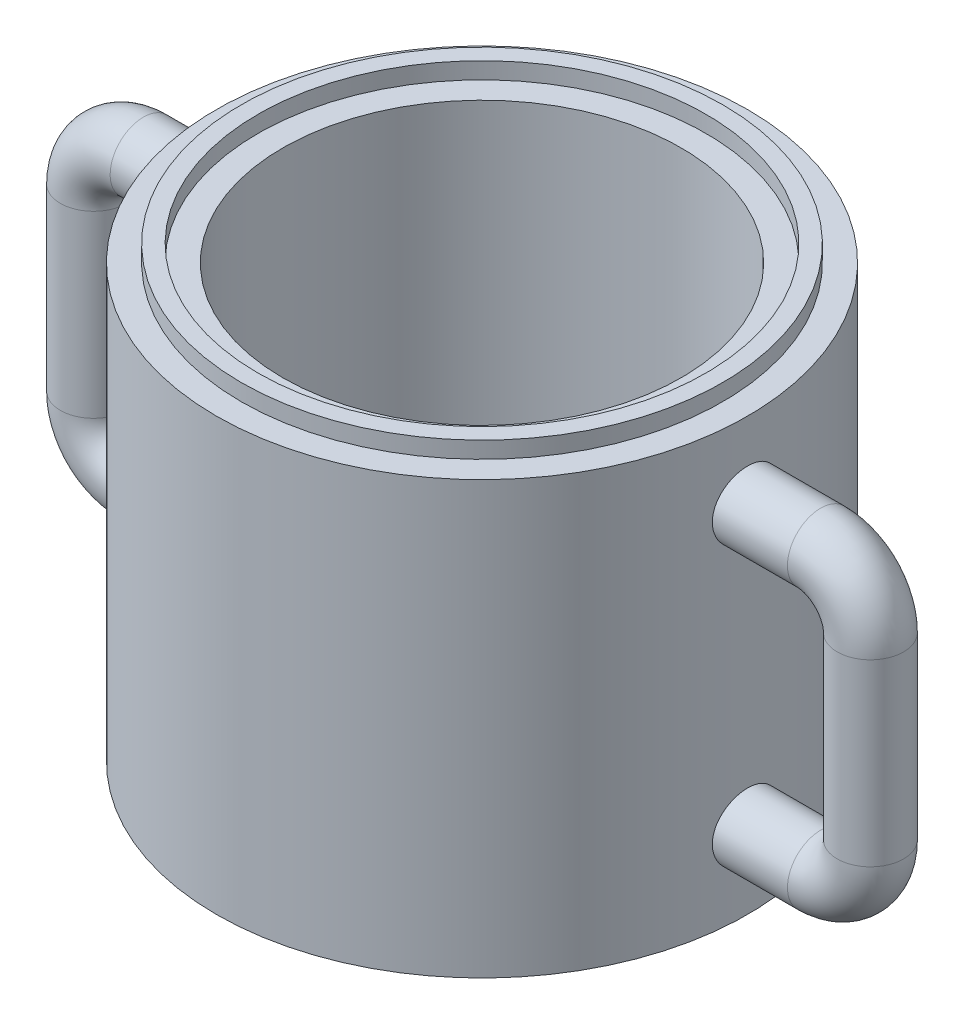
SolidWorks part; units mm, degrees
ref_plane "Plano frontal" through (0, 0, 0) normal (0, 0, 1) x (1, 0, 0)
ref_plane "Plano superior" through (0, 0, 0) normal (0, 1, 0) x (1, 0, 0)
ref_plane "Plano direito" through (0, 0, 0) normal (1, 0, 0) x (0, 0, -1)
sketch "Esboço1" plane through (0, 0, 0) normal (0, 1, 0) x (1, 0, 0)
  circle A0 centre (0, 0) radius 80
  dimension "D1" = 160
extrude "Ressalto-extrusão1" add sketch "Esboço1" along normal blind 130
sketch "Esboço2" plane through (0, 130, 0) normal (0, 1, 0) x (1, 0, 0)
  circle A0 centre (0, 0) radius 60
  dimension "D1" = 120
extrude "Corte-extrusão1" cut sketch "Esboço2" against normal blind 100
sketch "Esboço4" plane through (0, 0, 0) normal (1, 0, 0) x (0, 0, -1)
  line L0 (-80, 130) -> (-72.5, 130) construction
  line L2 (80, 130) -> (-80, 130) construction
  line L3 (-72.5, 130) -> (-67.5, 130) construction
  line L4 (-67.5, 130) -> (-60, 130) construction
  line L5 (-72.5, 130) -> (-72.5, 135)
  line L6 (-72.5, 135) -> (-67.5, 135)
  line L7 (-67.5, 135) -> (-67.5, 130)
  line L8 (-67.5, 130) -> (-72.5, 130)
  line L9 (0, 130) -> (0, 0) construction
  line L10 (60, 130) -> (-60, 130) construction
  dimension "D1" = 7.5
  dimension "D2" = 5
  dimension "D3" = 5
revolve "Revolução1" add sketch "Esboço4" angle 360 about L9
ref_plane "Plano1" through (70, 0, 0) normal (1, 0, 0) x (0, 0, -1)
sketch "Esboço5" plane through (70, 0, 0) normal (1, 0, 0) x (0, 0, -1)
  line L0 (-80, 130) -> (80, 130) construction
  line L1 (0, 130) -> (0, 0) construction
  line L2 (0, 65) -> (80, 65) construction
  line L3 (80, 0) -> (80, 130) construction
  circle A0 centre (0, 107) radius 12.5
  circle A1 centre (0, 23) radius 12.5
  dimension "D1" = 25
  dimension "D2" = 23
sketch "Esboço6" plane through (0, 0, 0) normal (0, 0, 1) x (1, 0, 0)
  line L0 (70, 107) -> (102, 107)
  line L1 (70, 23) -> (102, 23)
  line L2 (117, 92) -> (117, 38)
  arc A0 (102, 23) -> (117, 38) centre (102, 38) ccw
  arc A1 (102, 107) -> (117, 92) centre (102, 92) cw
  point P8 (117, 23)
  point P11 (117, 107)
  dimension "D3" = 15
  dimension "D1" = 47
  dimension "D2" = 47
sweep "Varredura2" add path "Esboço6" circular profile diameter 20 parameters "D3"=20
ref_plane "Plano2" through (-70, 0, 0) normal (1, 0, 0) x (0, 0, -1)
sketch "Esboço35" plane through (-70, 0, 0) normal (1, 0, 0) x (0, 0, -1)
  line L0 (-80, 130) -> (80, 130) construction
  line L1 (0, 130) -> (0, 107) construction
  line L2 (0, 23) -> (0, 0) construction
sketch "Esboço36" plane through (0, 0, 0) normal (0, 0, 1) x (1, 0, 0)
  line L0 (-70, 107) -> (-102, 107)
  line L2 (-70, 23) -> (-102, 23)
  line L3 (-117, 38) -> (-117, 92)
  arc A0 (-102, 23) -> (-117, 38) centre (-102, 38) cw
  arc A1 (-102, 107) -> (-117, 92) centre (-102, 92) ccw
  point P10 (-117, 107)
  dimension "D2" = 15
  dimension "D1" = 47
sweep "Varredura3" add path "Esboço36" circular profile diameter 20 parameters "D3"=20
